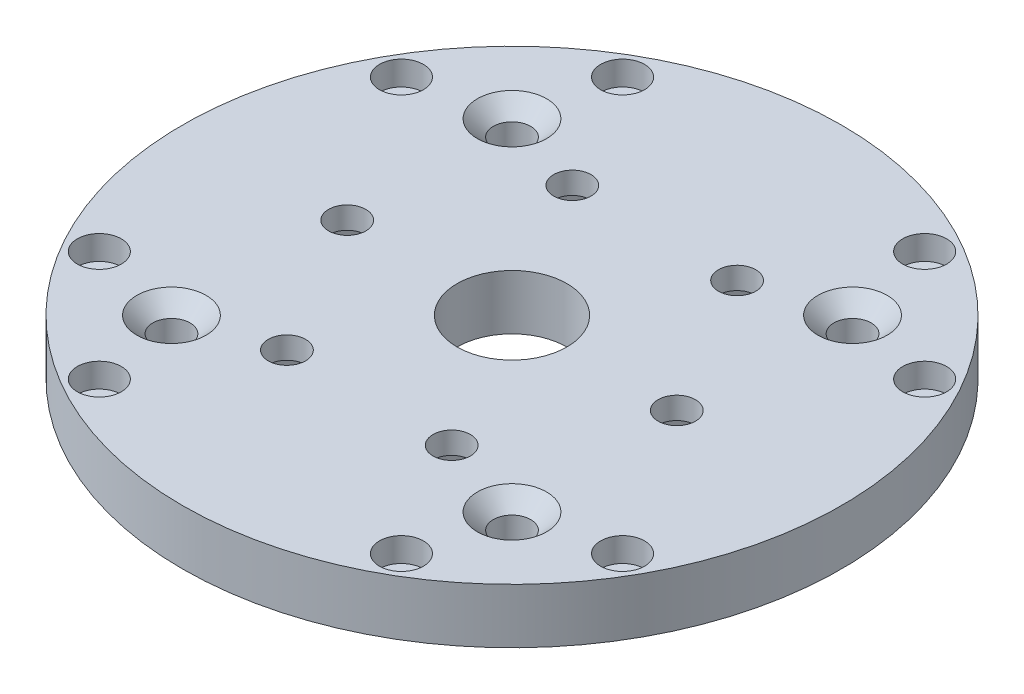
SolidWorks part; units mm, degrees
material "ABS"
ref_plane "Ön Düzlem" through (0, 0, 0) normal (0, 0, 1) x (1, 0, 0)
ref_plane "Üst Düzlem" through (0, 0, 0) normal (0, 1, 0) x (1, 0, 0)
ref_plane "Sağ Düzlem" through (0, 0, 0) normal (1, 0, 0) x (0, 0, -1)
sketch "Sketch1" plane through (0, 0, 0) normal (0, 1, 0) x (1, 0, 0)
  circle A0 centre (0, 0) radius 30
  dimension "D1" = 60
extrude "Boss-Extrude1" add sketch "Sketch1" along normal blind 5
sketch "Sketch2" plane through (0, 5, 0) normal (0, 1, 0) x (1, 0, 0)
  line L1 (-15.5, -15.5) -> (15.5, -15.5) construction
  line L2 (-15.5, -15.5) -> (-15.5, 15.5) construction
  line L3 (-15.5, 15.5) -> (15.5, 15.5) construction
  line L4 (15.5, -15.5) -> (15.5, 15.5) construction
  line L5 (-15.5, -15.5) -> (15.5, 15.5) construction
  line L6 (-15.5, 15.5) -> (15.5, -15.5) construction
  point P7 (15.5, 15.5)
  point P8 (-15.5, 15.5)
  point P9 (15.5, -15.5)
  point P10 (-15.5, -15.5)
  dimension "D1" = 31
hole_wizard "CSK for M3 Flat Head Machine Screw1" positions "Sketch2" profile "Sketch3" countersink size "M3" standard "ANSI Metric" end condition through all
sketch "Sketch3" plane through (-15.5, 5, 15.5) normal (1, 0, 0) x (0, 0, 1)
  line L0 (0, 0) -> (0, 5)
  line L1 (0, 5) -> (1.7, 5)
  line L2 (1.7, 5) -> (1.7, 1.45)
  line L3 (1.7, 1.45) -> (3.15, 0)
  line L5 (3.15, 0) -> (0, 0)
  line L6 (-1.7, 1.45) -> (-3.15, 0) construction
  line L11 (0, -6.35) -> (0, 107.95) construction
  dimension "Thru Hole Dia." = 3.4
  dimension "Thru Hole Depth" = 5
  dimension "Near C'Sink Dia." = 6.3
  dimension "Near C'Sink Angle" = 90
sketch "Sketch4" plane through (0, 5, 0) normal (0, 1, 0) x (1, 0, 0)
  line L0 (0, -32.1268) -> (0, 32.1268) construction
  line L1 (-32.2835, 0) -> (32.2835, 0) construction
  line L2 (0, 0) -> (-16.4059, 28.4159) construction
  circle A0 centre (-13.75, 23.8157) radius 1.1
  circle A8 centre (-23.8157, 13.75) radius 1.1
  circle A9 centre (13.75, 23.8157) radius 1.1
  circle A10 centre (23.8157, 13.75) radius 1.1
  circle A11 centre (23.8157, -13.75) radius 1.1
  circle A12 centre (13.75, -23.8157) radius 1.1
  circle A13 centre (-13.75, -23.8157) radius 1.1
  circle A14 centre (-23.8157, -13.75) radius 1.1
  point P4 (0, 0)
  point P8 (0, 0)
  point P15 (0, 0)
  point P16 (1.9983, 2.5313)
  point P29 (0, 0)
  point P31 (0, 0)
  dimension "D2" = 2.2
  dimension "D5" = 27.5
  dimension "D1" = 30
  dimension "D3" = 2
  dimension "D4" = 4
extrude "Cut-Extrude1" cut sketch "Sketch4" against normal up to next
sketch "Sketch5" plane through (0, 5, 0) normal (0, 1, 0) x (1, 0, 0)
  circle A0 centre (0, 0) radius 5
  dimension "D1" = 10
extrude "Cut-Extrude2" cut sketch "Sketch5" against normal up to next
sketch "Sketch7" plane through (0, 5, 0) normal (0, 1, 0) x (1, 0, 0)
  line L0 (0, -32.0484) -> (0, 32.0484) construction
  line L1 (-32.2835, 0) -> (32.2835, 0) construction
  circle A0 centre (-13.75, 23.8157) radius 2
  circle A1 centre (-23.8157, 13.75) radius 2
  circle A2 centre (13.75, 23.8157) radius 2
  circle A3 centre (23.8157, 13.75) radius 2
  circle A4 centre (23.8157, -13.75) radius 2
  circle A5 centre (13.75, -23.8157) radius 2
  circle A6 centre (-13.75, -23.8157) radius 2
  circle A7 centre (-23.8157, -13.75) radius 2
  point P5 (0, 0)
  point P9 (0, 0)
  point P16 (0, 0)
  point P30 (0, 0)
  dimension "D1" = 4
  dimension "D2" = 2
  dimension "D3" = 4
extrude "Cut-Extrude3" cut sketch "Sketch7" against normal blind 2.2
sketch "Sketch8" plane through (0, 0, 0) normal (0, 1, 0) x (1, 0, 0)
  line L0 (-9.0877, 15.7404) -> (-10.6754, 12.9904)
  line L1 (-18.1754, 0) -> (-16.5877, -2.75)
  line L2 (-16.5877, -2.75) -> (-13.4123, -2.75)
  line L3 (-13.4123, -2.75) -> (-11.8246, 0)
  line L4 (-11.8246, 0) -> (-13.4123, 2.75)
  line L5 (-13.4123, 2.75) -> (-16.5877, 2.75)
  line L6 (-16.5877, 2.75) -> (-18.1754, 0)
  line L7 (-10.6754, 12.9904) -> (-9.0877, 10.2404)
  line L8 (-9.0877, 10.2404) -> (-5.9123, 10.2404)
  line L9 (-5.9123, 10.2404) -> (-4.3246, 12.9904)
  line L10 (-4.3246, 12.9904) -> (-5.9123, 15.7404)
  line L11 (-5.9123, 15.7404) -> (-9.0877, 15.7404)
  line L12 (9.0877, 15.7404) -> (5.9123, 15.7404)
  line L13 (5.9123, 15.7404) -> (4.3246, 12.9904)
  line L14 (4.3246, 12.9904) -> (5.9123, 10.2404)
  line L15 (5.9123, 10.2404) -> (9.0877, 10.2404)
  line L16 (9.0877, 10.2404) -> (10.6754, 12.9904)
  line L17 (10.6754, 12.9904) -> (9.0877, 15.7404)
  line L18 (18.1754, 0) -> (16.5877, 2.75)
  line L19 (16.5877, 2.75) -> (13.4123, 2.75)
  line L20 (13.4123, 2.75) -> (11.8246, 0)
  line L21 (11.8246, 0) -> (13.4123, -2.75)
  line L22 (13.4123, -2.75) -> (16.5877, -2.75)
  line L23 (16.5877, -2.75) -> (18.1754, 0)
  line L24 (9.0877, -15.7404) -> (10.6754, -12.9904)
  line L25 (10.6754, -12.9904) -> (9.0877, -10.2404)
  line L26 (9.0877, -10.2404) -> (5.9123, -10.2404)
  line L27 (5.9123, -10.2404) -> (4.3246, -12.9904)
  line L28 (4.3246, -12.9904) -> (5.9123, -15.7404)
  line L29 (5.9123, -15.7404) -> (9.0877, -15.7404)
  line L30 (-9.0877, -15.7404) -> (-5.9123, -15.7404)
  line L31 (-5.9123, -15.7404) -> (-4.3246, -12.9904)
  line L32 (-4.3246, -12.9904) -> (-5.9123, -10.2404)
  line L33 (-5.9123, -10.2404) -> (-9.0877, -10.2404)
  line L34 (-9.0877, -10.2404) -> (-10.6754, -12.9904)
  line L35 (-10.6754, -12.9904) -> (-9.0877, -15.7404)
  circle A0 centre (0, 0) radius 15 construction
  circle A1 centre (-15, 0) radius 2.75 construction
  point P43 (0, 0)
  dimension "D1" = 30
  dimension "D2" = 5.5
  dimension "D3" = 6
extrude "Cut-Extrude4" cut sketch "Sketch8" along normal blind 3
sketch "Sketch9" plane through (0, 0, 0) normal (0, -1, 0) x (1, 0, 0)
  circle A0 centre (15, 0) radius 1.7
  circle A1 centre (7.5, -12.9904) radius 1.7
  circle A2 centre (-7.5, -12.9904) radius 1.7
  circle A3 centre (-15, 0) radius 1.7
  circle A4 centre (-7.5, 12.9904) radius 1.7
  circle A5 centre (7.5, 12.9904) radius 1.7
  point P16 (0, 0)
  dimension "D2" = 3.4
  dimension "D1" = 15
  dimension "D3" = 6
extrude "Cut-Extrude5" cut sketch "Sketch9" against normal through all
